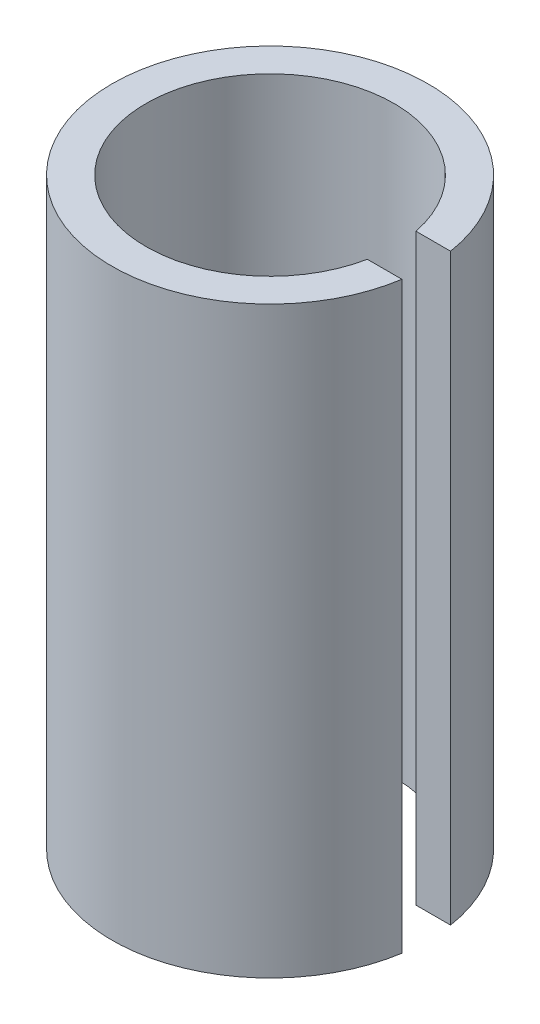
SolidWorks part; units mm, degrees
ref_plane "Front Plane" through (0, 0, 0) normal (0, 0, 1) x (1, 0, 0)
ref_plane "Top Plane" through (0, 0, 0) normal (0, 1, 0) x (1, 0, 0)
ref_plane "Right Plane" through (0, 0, 0) normal (1, 0, 0) x (0, 0, -1)
sketch "Sketch1" plane through (0, 0, 0) normal (0, 1, 0) x (1, 0, 0)
  line L0 (2.5005, 0.5) -> (3.2113, 0.5)
  line L1 (2.5005, -0.5) -> (3.2113, -0.5)
  line L2 (0, 0) -> (3.25, 0) construction
  circle A0 centre (0, 0) radius 3.25
  circle A1 centre (0, 0) radius 2.55
  dimension "D1" = 5.1
  dimension "D2" = 6.5
  dimension "D3" = 1
  dimension "D4" = 0.5
extrude "Boss-Extrude1" add sketch "Sketch1" along normal blind 12 contours A1 L0 A0 L1
